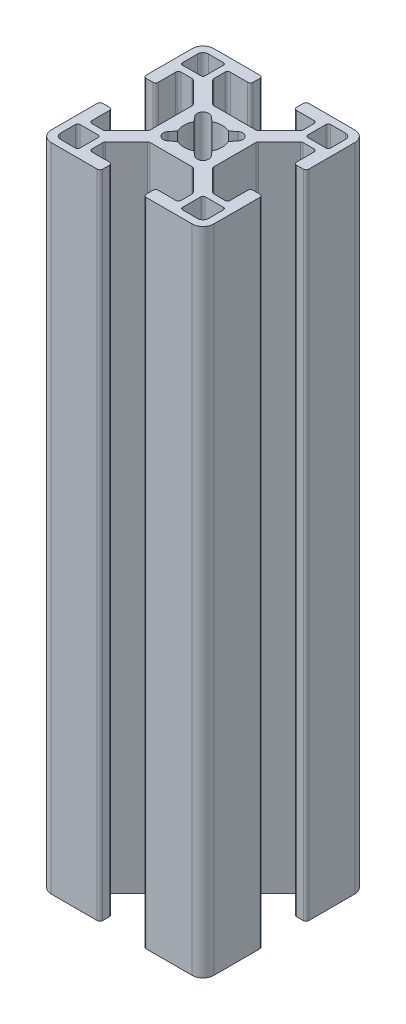
SolidWorks part; units mm, degrees
ref_plane "Front" through (0, 0, 0) normal (0, 0, 1) x (1, 0, 0)
ref_plane "Top" through (0, 0, 0) normal (0, 1, 0) x (1, 0, 0)
ref_plane "Right" through (0, 0, 0) normal (1, 0, 0) x (0, 0, -1)
sketch3d "3DSketch1"
  line L0 (0, 0, 0) -> (0, 120, 0)
  dimension "D1" = 120
other "Perfil com. aluminio PERFIL COMER. 30 X 30(1)"
ref_plane "Plano1" through (0, 0, 0) normal (0, 1, 0) x (1, 0, 0)
sketch "Esboço1" plane through (0, 0, 0) normal (0, 1, 0) x (1, 0, 0)
  line L10 (-3.1849, 1.488) -> (-3.9634, 2.4631)
  line L11 (-2.4631, 3.9634) -> (-1.488, 3.1849)
  line L16 (-9.46, 13.26) -> (-9.46, 9.84)
  line L17 (-9.84, 9.46) -> (-13.26, 9.46)
  line L18 (-13.64, 9.84) -> (-13.64, 12.64)
  line L19 (-12.64, 13.64) -> (-9.84, 13.64)
  line L44 (0, 5.8727) -> (-3.8729, 5.8727)
  line L45 (-4.2264, 6.0192) -> (-8.0736, 9.8663)
  line L46 (-8.22, 10.2198) -> (-8.22, 12.25)
  line L47 (-7.72, 12.75) -> (-4.5, 12.75)
  line L48 (-4, 13.25) -> (-4, 14.5)
  line L49 (-4.5, 15) -> (-13, 15)
  line L50 (-15, 13) -> (-15, 4.5)
  line L51 (-14.5, 4) -> (-13.25, 4)
  line L52 (-12.75, 4.5) -> (-12.75, 7.72)
  line L53 (-12.25, 8.22) -> (-10.2198, 8.22)
  line L54 (-9.8663, 8.0736) -> (-6.0192, 4.2264)
  line L55 (-5.8727, 3.8729) -> (-5.8727, 0)
  line L84 (13.64, 12.64) -> (13.64, 9.84)
  line L91 (15, 4.5) -> (15, 13)
  line L92 (13, 15) -> (4.5, 15)
  line L93 (4, 14.5) -> (4, 13.25)
  line L94 (4.5, 12.75) -> (7.72, 12.75)
  line L95 (8.22, 12.25) -> (8.22, 10.2198)
  line L96 (8.0736, 9.8663) -> (4.2264, 6.0192)
  line L97 (3.8729, 5.8727) -> (0, 5.8727)
  line L98 (1.488, 3.1849) -> (2.4631, 3.9634)
  line L99 (3.9634, 2.4631) -> (3.1849, 1.488)
  line L100 (5.8727, 0) -> (5.8727, 3.8729)
  line L101 (6.0192, 4.2264) -> (9.8663, 8.0736)
  line L102 (10.2198, 8.22) -> (12.25, 8.22)
  line L103 (12.75, 7.72) -> (12.75, 4.5)
  line L104 (13.25, 4) -> (14.5, 4)
  line L105 (13.26, 9.46) -> (9.84, 9.46)
  line L112 (9.46, 9.84) -> (9.46, 13.26)
  line L113 (9.84, 13.64) -> (12.64, 13.64)
  line L114 (12.64, -13.64) -> (9.84, -13.64)
  line L115 (4.5, -15) -> (13, -15)
  line L116 (15, -13) -> (15, -4.5)
  line L117 (14.5, -4) -> (13.25, -4)
  line L118 (12.75, -4.5) -> (12.75, -7.72)
  line L119 (12.25, -8.22) -> (10.2198, -8.22)
  line L120 (9.8663, -8.0736) -> (6.0192, -4.2264)
  line L121 (5.8727, -3.8729) -> (5.8727, 0)
  line L122 (3.1849, -1.488) -> (3.9634, -2.4631)
  line L123 (2.4631, -3.9634) -> (1.488, -3.1849)
  line L124 (0, -5.8727) -> (3.8729, -5.8727)
  line L125 (4.2264, -6.0192) -> (8.0736, -9.8663)
  line L126 (8.22, -10.2198) -> (8.22, -12.25)
  line L133 (7.72, -12.75) -> (4.5, -12.75)
  line L134 (4, -13.25) -> (4, -14.5)
  line L135 (9.46, -13.26) -> (9.46, -9.84)
  line L136 (9.84, -9.46) -> (13.26, -9.46)
  line L137 (13.64, -9.84) -> (13.64, -12.64)
  line L138 (-13.64, -12.64) -> (-13.64, -9.84)
  line L139 (-15, -4.5) -> (-15, -13)
  line L140 (-13, -15) -> (-4.5, -15)
  line L141 (-4, -14.5) -> (-4, -13.25)
  line L142 (-4.5, -12.75) -> (-7.72, -12.75)
  line L143 (-8.22, -12.25) -> (-8.22, -10.2198)
  line L144 (-8.0736, -9.8663) -> (-4.2264, -6.0192)
  line L145 (-3.8729, -5.8727) -> (0, -5.8727)
  line L146 (-1.488, -3.1849) -> (-2.4631, -3.9634)
  line L147 (-3.9634, -2.4631) -> (-3.1849, -1.488)
  line L148 (3.9634, 2.4631) -> (3.1849, 1.488) [skipped]
  line L149 (13.26, 9.46) -> (9.84, 9.46) [skipped]
  line L150 (9.46, 9.84) -> (9.46, 13.26) [skipped]
  line L151 (9.84, 13.64) -> (12.64, 13.64) [skipped]
  line L152 (13.64, 12.64) -> (13.64, 9.84) [skipped]
  line L153 (5.8727, 0) -> (5.8727, 3.8729) [skipped]
  line L154 (6.0192, 4.2264) -> (9.8663, 8.0736) [skipped]
  line L155 (10.2198, 8.22) -> (12.25, 8.22) [skipped]
  line L156 (12.75, 7.72) -> (12.75, 4.5) [skipped]
  line L157 (13.25, 4) -> (14.5, 4) [skipped]
  line L158 (15, 4.5) -> (15, 13) [skipped]
  line L159 (13, 15) -> (4.5, 15) [skipped]
  line L160 (4, 14.5) -> (4, 13.25) [skipped]
  line L161 (4.5, 12.75) -> (7.72, 12.75) [skipped]
  line L162 (8.22, 12.25) -> (8.22, 10.2198) [skipped]
  line L163 (8.0736, 9.8663) -> (4.2264, 6.0192) [skipped]
  line L164 (3.8729, 5.8727) -> (0, 5.8727) [skipped]
  line L165 (3.1849, -1.488) -> (3.9634, -2.4631) [skipped]
  line L166 (9.46, -13.26) -> (9.46, -9.84) [skipped]
  line L167 (9.84, -9.46) -> (13.26, -9.46) [skipped]
  line L168 (13.64, -9.84) -> (13.64, -12.64) [skipped]
  line L169 (12.64, -13.64) -> (9.84, -13.64) [skipped]
  line L170 (0, -5.8727) -> (3.8729, -5.8727) [skipped]
  line L171 (4.2264, -6.0192) -> (8.0736, -9.8663) [skipped]
  line L172 (8.22, -10.2198) -> (8.22, -12.25) [skipped]
  line L173 (7.72, -12.75) -> (4.5, -12.75) [skipped]
  line L174 (4, -13.25) -> (4, -14.5) [skipped]
  line L175 (4.5, -15) -> (13, -15) [skipped]
  line L176 (15, -13) -> (15, -4.5) [skipped]
  line L177 (14.5, -4) -> (13.25, -4) [skipped]
  line L178 (12.75, -4.5) -> (12.75, -7.72) [skipped]
  line L179 (12.25, -8.22) -> (10.2198, -8.22) [skipped]
  line L180 (9.8663, -8.0736) -> (6.0192, -4.2264) [skipped]
  line L181 (5.8727, -3.8729) -> (5.8727, 0) [skipped]
  line L182 (-9.46, -9.84) -> (-9.46, -13.26) [skipped]
  line L183 (-9.84, -13.64) -> (-12.64, -13.64) [skipped]
  line L184 (-13.64, -12.64) -> (-13.64, -9.84) [skipped]
  line L185 (-15, -4.5) -> (-15, -13) [skipped]
  line L186 (-13, -15) -> (-4.5, -15) [skipped]
  line L187 (-4, -14.5) -> (-4, -13.25) [skipped]
  line L188 (-4.5, -12.75) -> (-7.72, -12.75) [skipped]
  line L189 (-8.22, -12.25) -> (-8.22, -10.2198) [skipped]
  line L190 (2.4631, -3.9634) -> (1.488, -3.1849) [skipped]
  line L191 (-1.488, -3.1849) -> (-2.4631, -3.9634) [skipped]
  line L192 (-13.26, -9.46) -> (-9.84, -9.46) [skipped]
  line L193 (-6.0192, -4.2264) -> (-9.8663, -8.0736) [skipped]
  line L194 (-10.2198, -8.22) -> (-12.25, -8.22) [skipped]
  line L195 (-12.75, -7.72) -> (-12.75, -4.5) [skipped]
  line L196 (-13.25, -4) -> (-14.5, -4) [skipped]
  line L197 (-8.0736, -9.8663) -> (-4.2264, -6.0192) [skipped]
  line L198 (-3.8729, -5.8727) -> (0, -5.8727) [skipped]
  line L199 (1.488, 3.1849) -> (2.4631, 3.9634) [skipped]
  line L200 (-3.9634, -2.4631) -> (-3.1849, -1.488) [skipped]
  line L201 (-5.8727, 0) -> (-5.8727, -3.8729) [skipped]
  line L202 (-5.8727, 0) -> (-5.8727, -3.8729)
  line L203 (-6.0192, -4.2264) -> (-9.8663, -8.0736)
  line L204 (-10.2198, -8.22) -> (-12.25, -8.22)
  line L205 (-12.75, -7.72) -> (-12.75, -4.5)
  line L206 (-13.25, -4) -> (-14.5, -4)
  line L207 (-13.26, -9.46) -> (-9.84, -9.46)
  line L208 (-9.46, -9.84) -> (-9.46, -13.26)
  line L209 (-9.84, -13.64) -> (-12.64, -13.64)
  arc A10 (-3.1849, 1.488) -> (-3.5154, 0) centre (0, 0) ccw
  arc A11 (-2.4631, 3.9634) -> (-3.9634, 2.4631) centre (-3.1292, 3.1292) ccw
  arc A12 (0, 3.5154) -> (-1.488, 3.1849) centre (0, 0) ccw
  arc A16 (-9.46, 13.26) -> (-9.84, 13.64) centre (-9.84, 13.26) ccw
  arc A17 (-9.84, 9.46) -> (-9.46, 9.84) centre (-9.84, 9.84) ccw
  arc A18 (-13.64, 9.84) -> (-13.26, 9.46) centre (-13.26, 9.84) ccw
  arc A19 (-12.64, 13.64) -> (-13.64, 12.64) centre (-12.64, 12.64) ccw
  arc A41 (-7.72, 12.75) -> (-8.22, 12.25) centre (-7.72, 12.25) ccw
  arc A42 (-4.5, 12.75) -> (-4, 13.25) centre (-4.5, 13.25) ccw
  arc A43 (-4, 14.5) -> (-4.5, 15) centre (-4.5, 14.5) ccw
  arc A44 (-13, 15) -> (-15, 13) centre (-13, 13) ccw
  arc A45 (-15, 4.5) -> (-14.5, 4) centre (-14.5, 4.5) ccw
  arc A46 (-13.25, 4) -> (-12.75, 4.5) centre (-13.25, 4.5) ccw
  arc A47 (-12.25, 8.22) -> (-12.75, 7.72) centre (-12.25, 7.72) ccw
  arc A50 (-6.0192, 4.2264) -> (-5.8727, 3.8729) centre (-6.3727, 3.8729) cw
  arc A51 (-4.2264, 6.0192) -> (-3.8729, 5.8727) centre (-3.8729, 6.3727) ccw
  arc A52 (-8.22, 10.2198) -> (-8.0736, 9.8663) centre (-7.72, 10.2198) ccw
  arc A53 (-10.2198, 8.22) -> (-9.8663, 8.0736) centre (-10.2198, 7.72) cw
  arc A68 (15, 13) -> (13, 15) centre (13, 13) ccw
  arc A69 (13.64, 12.64) -> (12.64, 13.64) centre (12.64, 12.64) ccw
  arc A70 (4.5, 15) -> (4, 14.5) centre (4.5, 14.5) ccw
  arc A71 (4, 13.25) -> (4.5, 12.75) centre (4.5, 13.25) ccw
  arc A79 (8.22, 12.25) -> (7.72, 12.75) centre (7.72, 12.25) ccw
  arc A80 (8.22, 10.2198) -> (8.0736, 9.8663) centre (7.72, 10.2198) cw
  arc A81 (4.2264, 6.0192) -> (3.8729, 5.8727) centre (3.8729, 6.3727) cw
  arc A82 (1.488, 3.1849) -> (0, 3.5154) centre (0, 0) ccw
  arc A83 (3.9634, 2.4631) -> (2.4631, 3.9634) centre (3.1292, 3.1292) ccw
  arc A84 (3.5154, 0) -> (3.1849, 1.488) centre (0, 0) ccw
  arc A85 (6.0192, 4.2264) -> (5.8727, 3.8729) centre (6.3727, 3.8729) ccw
  arc A86 (10.2198, 8.22) -> (9.8663, 8.0736) centre (10.2198, 7.72) ccw
  arc A87 (12.75, 7.72) -> (12.25, 8.22) centre (12.25, 7.72) ccw
  arc A88 (12.75, 4.5) -> (13.25, 4) centre (13.25, 4.5) ccw
  arc A89 (14.5, 4) -> (15, 4.5) centre (14.5, 4.5) ccw
  arc A97 (13.26, 9.46) -> (13.64, 9.84) centre (13.26, 9.84) ccw
  arc A98 (9.46, 9.84) -> (9.84, 9.46) centre (9.84, 9.84) ccw
  arc A99 (9.84, 13.64) -> (9.46, 13.26) centre (9.84, 13.26) ccw
  arc A100 (13, -15) -> (15, -13) centre (13, -13) ccw
  arc A101 (12.64, -13.64) -> (13.64, -12.64) centre (12.64, -12.64) ccw
  arc A102 (15, -4.5) -> (14.5, -4) centre (14.5, -4.5) ccw
  arc A103 (13.25, -4) -> (12.75, -4.5) centre (13.25, -4.5) ccw
  arc A104 (12.25, -8.22) -> (12.75, -7.72) centre (12.25, -7.72) ccw
  arc A105 (10.2198, -8.22) -> (9.8663, -8.0736) centre (10.2198, -7.72) cw
  arc A106 (6.0192, -4.2264) -> (5.8727, -3.8729) centre (6.3727, -3.8729) cw
  arc A107 (3.1849, -1.488) -> (3.5154, 0) centre (0, 0) ccw
  arc A108 (3.9634, 2.4631) -> (2.4631, 3.9634) centre (3.1292, 3.1292) ccw [skipped]
  arc A109 (13.26, 9.46) -> (13.64, 9.84) centre (13.26, 9.84) ccw [skipped]
  arc A110 (9.46, 9.84) -> (9.84, 9.46) centre (9.84, 9.84) ccw [skipped]
  arc A111 (9.84, 13.64) -> (9.46, 13.26) centre (9.84, 13.26) ccw [skipped]
  arc A112 (13.64, 12.64) -> (12.64, 13.64) centre (12.64, 12.64) ccw [skipped]
  arc A113 (12.75, 7.72) -> (12.25, 8.22) centre (12.25, 7.72) ccw [skipped]
  arc A114 (12.75, 4.5) -> (13.25, 4) centre (13.25, 4.5) ccw [skipped]
  arc A115 (14.5, 4) -> (15, 4.5) centre (14.5, 4.5) ccw [skipped]
  arc A116 (15, 13) -> (13, 15) centre (13, 13) ccw [skipped]
  arc A117 (4.5, 15) -> (4, 14.5) centre (4.5, 14.5) ccw [skipped]
  arc A118 (4, 13.25) -> (4.5, 12.75) centre (4.5, 13.25) ccw [skipped]
  arc A119 (8.22, 12.25) -> (7.72, 12.75) centre (7.72, 12.25) ccw [skipped]
  arc A120 (4.2264, 6.0192) -> (3.8729, 5.8727) centre (3.8729, 6.3727) cw [skipped]
  arc A121 (6.0192, 4.2264) -> (5.8727, 3.8729) centre (6.3727, 3.8729) ccw [skipped]
  arc A122 (10.2198, 8.22) -> (9.8663, 8.0736) centre (10.2198, 7.72) ccw [skipped]
  arc A123 (8.22, 10.2198) -> (8.0736, 9.8663) centre (7.72, 10.2198) cw [skipped]
  arc A124 (2.4631, -3.9634) -> (3.9634, -2.4631) centre (3.1292, -3.1292) ccw [skipped]
  arc A125 (9.46, -13.26) -> (9.84, -13.64) centre (9.84, -13.26) ccw [skipped]
  arc A126 (9.84, -9.46) -> (9.46, -9.84) centre (9.84, -9.84) ccw [skipped]
  arc A127 (13.64, -9.84) -> (13.26, -9.46) centre (13.26, -9.84) ccw [skipped]
  arc A128 (12.64, -13.64) -> (13.64, -12.64) centre (12.64, -12.64) ccw [skipped]
  arc A129 (7.72, -12.75) -> (8.22, -12.25) centre (7.72, -12.25) ccw [skipped]
  arc A130 (4.5, -12.75) -> (4, -13.25) centre (4.5, -13.25) ccw [skipped]
  arc A131 (4, -14.5) -> (4.5, -15) centre (4.5, -14.5) ccw [skipped]
  arc A132 (13, -15) -> (15, -13) centre (13, -13) ccw [skipped]
  arc A133 (15, -4.5) -> (14.5, -4) centre (14.5, -4.5) ccw [skipped]
  arc A134 (13.25, -4) -> (12.75, -4.5) centre (13.25, -4.5) ccw [skipped]
  arc A135 (12.25, -8.22) -> (12.75, -7.72) centre (12.25, -7.72) ccw [skipped]
  arc A136 (6.0192, -4.2264) -> (5.8727, -3.8729) centre (6.3727, -3.8729) cw [skipped]
  arc A137 (4.2264, -6.0192) -> (3.8729, -5.8727) centre (3.8729, -6.3727) ccw [skipped]
  arc A138 (8.22, -10.2198) -> (8.0736, -9.8663) centre (7.72, -10.2198) ccw [skipped]
  arc A139 (10.2198, -8.22) -> (9.8663, -8.0736) centre (10.2198, -7.72) cw [skipped]
  arc A140 (-9.84, -13.64) -> (-9.46, -13.26) centre (-9.84, -13.26) ccw [skipped]
  arc A141 (-13.64, -12.64) -> (-12.64, -13.64) centre (-12.64, -12.64) ccw [skipped]
  arc A142 (-15, -13) -> (-13, -15) centre (-13, -13) ccw [skipped]
  arc A143 (-4.5, -15) -> (-4, -14.5) centre (-4.5, -14.5) ccw [skipped]
  arc A144 (-4, -13.25) -> (-4.5, -12.75) centre (-4.5, -13.25) ccw [skipped]
  arc A145 (-8.22, -12.25) -> (-7.72, -12.75) centre (-7.72, -12.25) ccw [skipped]
  arc A146 (0, -3.5154) -> (1.488, -3.1849) centre (0, 0) ccw [skipped]
  arc A147 (-1.488, -3.1849) -> (0, -3.5154) centre (0, 0) ccw [skipped]
  arc A148 (-3.9634, -2.4631) -> (-2.4631, -3.9634) centre (-3.1292, -3.1292) ccw [skipped]
  arc A149 (-13.26, -9.46) -> (-13.64, -9.84) centre (-13.26, -9.84) ccw [skipped]
  arc A150 (-9.46, -9.84) -> (-9.84, -9.46) centre (-9.84, -9.84) ccw [skipped]
  arc A151 (-12.75, -7.72) -> (-12.25, -8.22) centre (-12.25, -7.72) ccw [skipped]
  arc A152 (-12.75, -4.5) -> (-13.25, -4) centre (-13.25, -4.5) ccw [skipped]
  arc A153 (-14.5, -4) -> (-15, -4.5) centre (-14.5, -4.5) ccw [skipped]
  arc A154 (-4.2264, -6.0192) -> (-3.8729, -5.8727) centre (-3.8729, -6.3727) cw [skipped]
  arc A155 (-6.0192, -4.2264) -> (-5.8727, -3.8729) centre (-6.3727, -3.8729) ccw [skipped]
  arc A156 (-10.2198, -8.22) -> (-9.8663, -8.0736) centre (-10.2198, -7.72) ccw [skipped]
  arc A157 (-8.22, -10.2198) -> (-8.0736, -9.8663) centre (-7.72, -10.2198) cw [skipped]
  arc A158 (3.5154, 0) -> (3.1849, 1.488) centre (0, 0) ccw [skipped]
  arc A159 (3.1849, -1.488) -> (3.5154, 0) centre (0, 0) ccw [skipped]
  arc A160 (1.488, 3.1849) -> (0, 3.5154) centre (0, 0) ccw [skipped]
  arc A161 (-3.5154, 0) -> (-3.1849, -1.488) centre (0, 0) ccw [skipped]
  arc A162 (2.4631, -3.9634) -> (3.9634, -2.4631) centre (3.1292, -3.1292) ccw
  arc A163 (0, -3.5154) -> (1.488, -3.1849) centre (0, 0) ccw
  arc A164 (4.2264, -6.0192) -> (3.8729, -5.8727) centre (3.8729, -6.3727) ccw
  arc A165 (8.22, -10.2198) -> (8.0736, -9.8663) centre (7.72, -10.2198) ccw
  arc A166 (7.72, -12.75) -> (8.22, -12.25) centre (7.72, -12.25) ccw
  arc A167 (4.5, -12.75) -> (4, -13.25) centre (4.5, -13.25) ccw
  arc A168 (4, -14.5) -> (4.5, -15) centre (4.5, -14.5) ccw
  arc A169 (9.46, -13.26) -> (9.84, -13.64) centre (9.84, -13.26) ccw
  arc A170 (9.84, -9.46) -> (9.46, -9.84) centre (9.84, -9.84) ccw
  arc A171 (13.64, -9.84) -> (13.26, -9.46) centre (13.26, -9.84) ccw
  arc A172 (-15, -13) -> (-13, -15) centre (-13, -13) ccw
  arc A173 (-13.64, -12.64) -> (-12.64, -13.64) centre (-12.64, -12.64) ccw
  arc A174 (-4.5, -15) -> (-4, -14.5) centre (-4.5, -14.5) ccw
  arc A175 (-4, -13.25) -> (-4.5, -12.75) centre (-4.5, -13.25) ccw
  arc A176 (-8.22, -12.25) -> (-7.72, -12.75) centre (-7.72, -12.25) ccw
  arc A177 (-8.22, -10.2198) -> (-8.0736, -9.8663) centre (-7.72, -10.2198) cw
  arc A178 (-4.2264, -6.0192) -> (-3.8729, -5.8727) centre (-3.8729, -6.3727) cw
  arc A179 (-1.488, -3.1849) -> (0, -3.5154) centre (0, 0) ccw
  arc A180 (-3.9634, -2.4631) -> (-2.4631, -3.9634) centre (-3.1292, -3.1292) ccw
  arc A181 (-3.5154, 0) -> (-3.1849, -1.488) centre (0, 0) ccw
  arc A182 (-6.0192, -4.2264) -> (-5.8727, -3.8729) centre (-6.3727, -3.8729) ccw
  arc A183 (-10.2198, -8.22) -> (-9.8663, -8.0736) centre (-10.2198, -7.72) ccw
  arc A184 (-12.75, -7.72) -> (-12.25, -8.22) centre (-12.25, -7.72) ccw
  arc A185 (-12.75, -4.5) -> (-13.25, -4) centre (-13.25, -4.5) ccw
  arc A186 (-14.5, -4) -> (-15, -4.5) centre (-14.5, -4.5) ccw
  arc A187 (-13.26, -9.46) -> (-13.64, -9.84) centre (-13.26, -9.84) ccw
  arc A188 (-9.46, -9.84) -> (-9.84, -9.46) centre (-9.84, -9.84) ccw
  arc A189 (-9.84, -13.64) -> (-9.46, -13.26) centre (-9.84, -13.26) ccw
  point P0 (-8.75, 15)
  point P9 (0, 0)
  point P12 (-4.08, 5.8727)
  point P15 (-8.22, 10.0127)
  point P18 (-10.0127, 8.22)
  point P93 (0, 0)
  point P171 (0, 0)
  point P221 (0, 0)
  point P232 (0, 0)
  point P233 (0, 0)
  point P450 (0, 0)
  dimension "D3" = 1.0675
  dimension "D6" = 1.36
  dimension "D9" = 0.38
  dimension "D10" = 1
  dimension "D11" = 2
  dimension "D17" = 135
  dimension "D18" = 1.24
  dimension "D25" = 3.5154
  dimension "D39" = 0.5
  dimension "D20" = 15
  dimension "D26" = 0.5
  dimension "D4" = 167.212
  dimension "D5" = 25.043
  dimension "D7" = 1.36
  dimension "D8" = 4.18
  dimension "D12" = 4.18
  dimension "D13" = 1.24
  dimension "D14" = 2.25
  dimension "D15" = 11
  dimension "D16" = 11
  dimension "D19" = 15
  dimension "D21" = 4.14
  dimension "D22" = 38.606
  dimension "D23" = 25.043
  dimension "D24" = 38.606
  dimension "D27" = 5.8727
  dimension "D28" = 4
  dimension "D29" = 1.2477
  dimension "D30" = 4
  dimension "D33" = 135
  dimension "D38" = 0.5
hole_wizard "Durchgangsloch für M51" positions "3DSketch2" profile "Esboço3" hole size "M5" standard "DIN" end condition through all
sketch3d "3DSketch2"
  line L0 (-3.8729, 120, 5.8727) -> (3.8729, 120, 5.8727) construction
  point P0 (0, 90, 5.8727)
  point P2 (0, 40, 5.8727)
  point P8 (0, 120, 5.8727)
  dimension "D1" = 30
  dimension "D2" = 50
sketch "Esboço3" plane through (0, 90, 5.8727) normal (1, 0, 0) x (0, -1, 0)
  line L0 (0, 0) -> (0, 20.8727)
  line L1 (0, 20.8727) -> (2.65, 20.8727)
  line L2 (2.65, 20.8727) -> (2.65, 0)
  line L5 (2.65, 0) -> (0, 0)
  line L11 (0, -6.35) -> (0, 107.95) construction
  dimension "Thru Hole Dia." = 5.3
  dimension "Thru Hole Depth" = 20.8727
sketch "Esboço4" plane through (5.8727, 0, 0) normal (1, 0, 0) x (0, 0, -1)
  line L0 (-3.8729, 120) -> (3.8729, 120) construction
  circle A0 centre (0, 90) radius 2.5
  circle A1 centre (0, 40) radius 2.5
  point P4 (0, 0)
  point P5 (0, 0)
  point P8 (0, 120)
  dimension "D1" = 5
  dimension "D3" = 50
  dimension "D2" = 30
extrude "Corte-extrusão1" cut sketch "Esboço4" against normal through all
